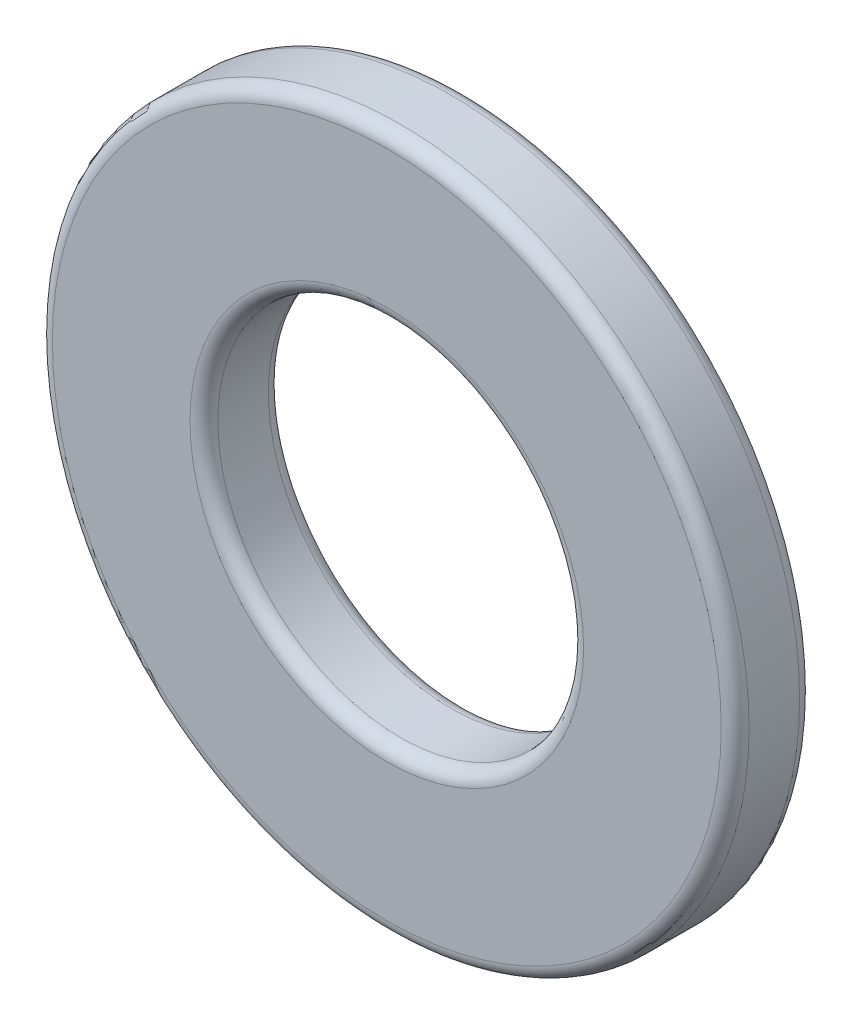
SolidWorks part; units mm, degrees
ref_plane "Front Plane" through (0, 0, 0) normal (0, 0, 1) x (1, 0, 0)
ref_plane "Top Plane" through (0, 0, 0) normal (0, 1, 0) x (1, 0, 0)
ref_plane "Right Plane" through (0, 0, 0) normal (1, 0, 0) x (0, 0, -1)
sketch "Sketch1" plane through (0, 0, 0) normal (0, 0, 1) x (1, 0, 0)
  circle A0 centre (0, 0) radius 8 construction
  circle A1 centre (0, 0) radius 4.2 construction
  point P5 (0, -8)
  dimension "OD" = 16
  dimension "ID" = 8.4
sketch "Sketch2" plane through (0, 0, 0) normal (1, 0, 0) x (0, 0, -1)
  line L0 (0.7, 0) -> (-0.7, 0) construction
  line L1 (-0.9, -8) -> (0.9, -8) construction
  point P0 (-0.9, -8)
  point P3 (0.9, -8)
  point P4 (0, 0)
  point P9 (0, -8)
  point P10 (-0.7, -8)
  point P11 (-0.9, -8)
  point P12 (0.7, -8)
  point P13 (0.9, -8)
  dimension "Thickness Range [Min]" = 1.4
  dimension "Thickness Range [Max]" = 1.8
sketch "Sketch3" plane through (0, 0, 0) normal (0, 0, 1) x (1, 0, 0)
  circle A0 centre (0, 0) radius 4.2 construction
  circle A1 centre (0, 0) radius 8 construction
  circle A2 centre (0, 0) radius 4.2
  circle A3 centre (0, 0) radius 8
extrude "Boss-Extrude1" add sketch "Sketch3" against normal up to vertex (0.9 mm away) and the other way up to vertex (0.9 mm away) up to point (0, -8, -0.9) other way up to point (0, -8, 0.9)
fillet "Fillet1" radius 0.32 4 edges at (8, 0, -0.9) (4.2, 0, -0.9) (4.2, 0, 0.9) (8, 0, 0.9)
equation "\"D1@Fillet1\"=\"OD@Sketch1\"*.02"
